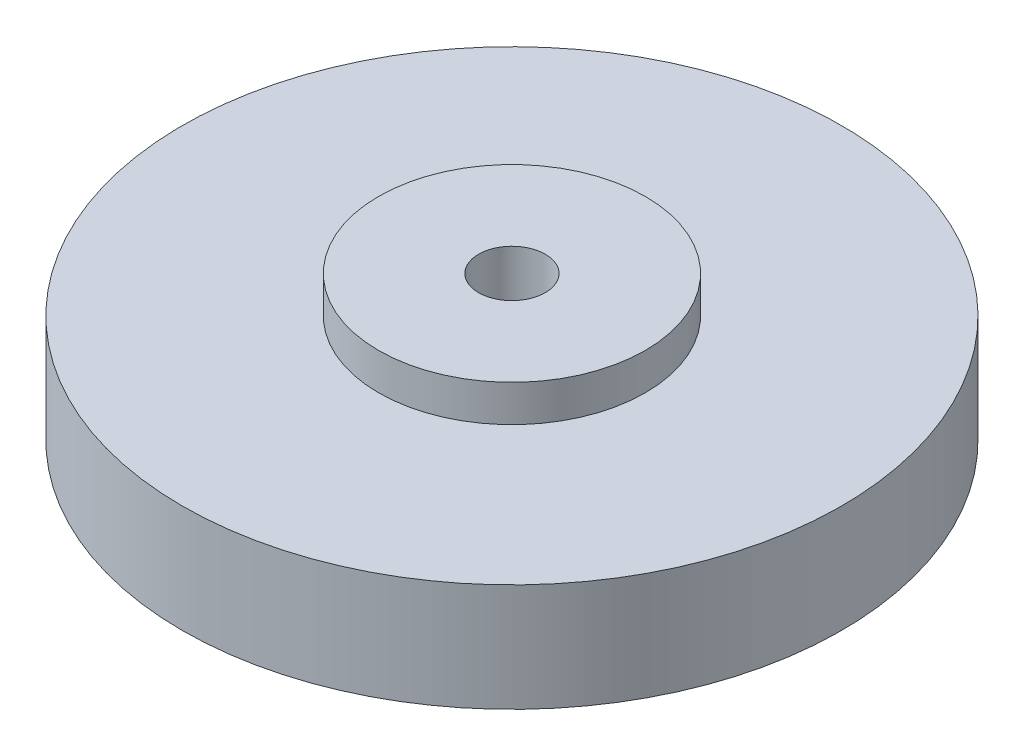
SolidWorks part; units mm, degrees
ref_plane "Front Plane" through (0, 0, 0) normal (0, 0, 1) x (1, 0, 0)
ref_plane "Top Plane" through (0, 0, 0) normal (0, 1, 0) x (1, 0, 0)
ref_plane "Right Plane" through (0, 0, 0) normal (1, 0, 0) x (0, 0, -1)
sketch "Sketch1" plane through (0, 0, 0) normal (0, 1, 0) x (1, 0, 0)
  circle A0 centre (0, 0) radius 14.825
extrude "Boss-Extrude1" add sketch "Sketch1" along normal blind 4.85
sketch "Sketch2" plane through (0, 4.85, 0) normal (0, 1, 0) x (1, 0, 0)
  circle A0 centre (0, 0) radius 6
extrude "Boss-Extrude2" add sketch "Sketch2" along normal blind 1.65
sketch "Sketch3" plane through (0, 6.5, 0) normal (0, 1, 0) x (1, 0, 0)
  circle A0 centre (0, 0) radius 1.5
extrude "Cut-Extrude1" cut sketch "Sketch3" against normal through all
